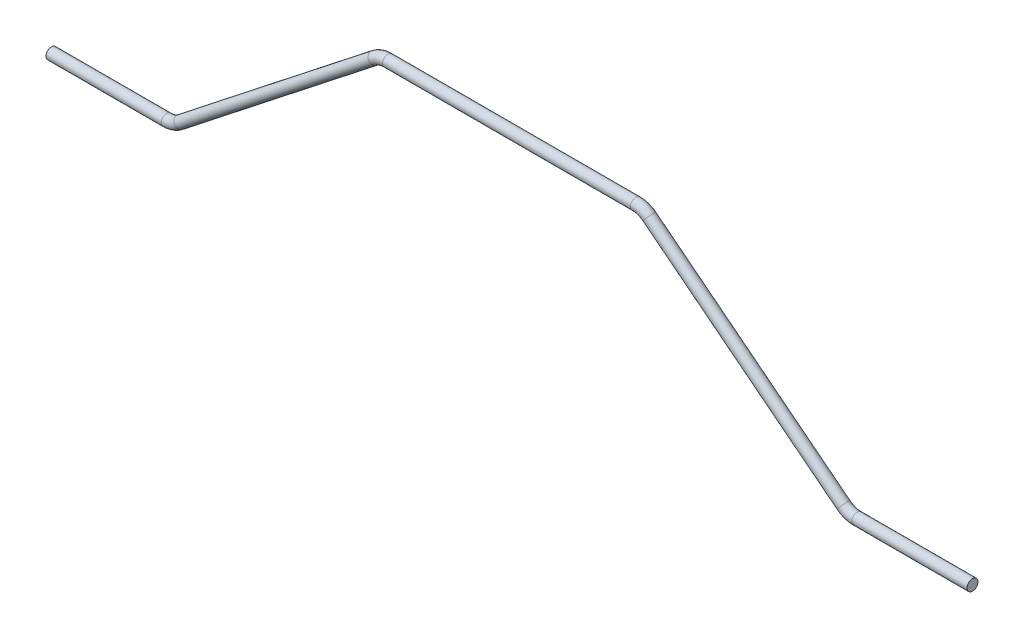
SolidWorks part; units mm, degrees
ref_plane "Front Plane" through (0, 0, 0) normal (0, 0, 1) x (1, 0, 0)
ref_plane "Top Plane" through (0, 0, 0) normal (0, 1, 0) x (1, 0, 0)
ref_plane "Right Plane" through (0, 0, 0) normal (1, 0, 0) x (0, 0, -1)
sketch "Sketch1" plane through (0, 0, 0) normal (0, 0, 1) x (1, 0, 0)
  line L0 (-56.5403, 0) -> (56.5403, 0)
  line L1 (62.72, -2.138) -> (151.28, -71.7477)
  line L2 (157.4597, -73.8857) -> (210, -73.8857)
  line L3 (0, 0) -> (0, -176.8485) construction
  line L4 (-157.4597, -73.8857) -> (-210, -73.8857)
  line L5 (-62.72, -2.138) -> (-151.28, -71.7477)
  arc A0 (157.4597, -73.8857) -> (151.28, -71.7477) centre (157.4597, -63.8857) cw
  arc A1 (62.72, -2.138) -> (56.5403, 0) centre (56.5403, -10) ccw
  arc A2 (-62.72, -2.138) -> (-56.5403, 0) centre (-56.5403, -10) cw
  arc A3 (-157.4597, -73.8857) -> (-151.28, -71.7477) centre (-157.4597, -63.8857) ccw
  point P10 (60, 0)
  dimension "D3" = 10
  dimension "D1" = 60
  dimension "D2" = 210
ref_plane "Plane1" through (210, -73.8857, 0) normal (1, 0, 0) x (0, 0, -1)
sketch "Sketch2" plane through (210, -73.8857, 0) normal (1, 0, 0) x (0, 0, -1)
  line L0 (0, 73.8857) -> (0, -102.9627) construction
  circle A0 centre (0, -0.0425) radius 2.5
  dimension "D2" = 5
sweep "Sweep1" add profiles "Sketch2" path "Sketch1"
